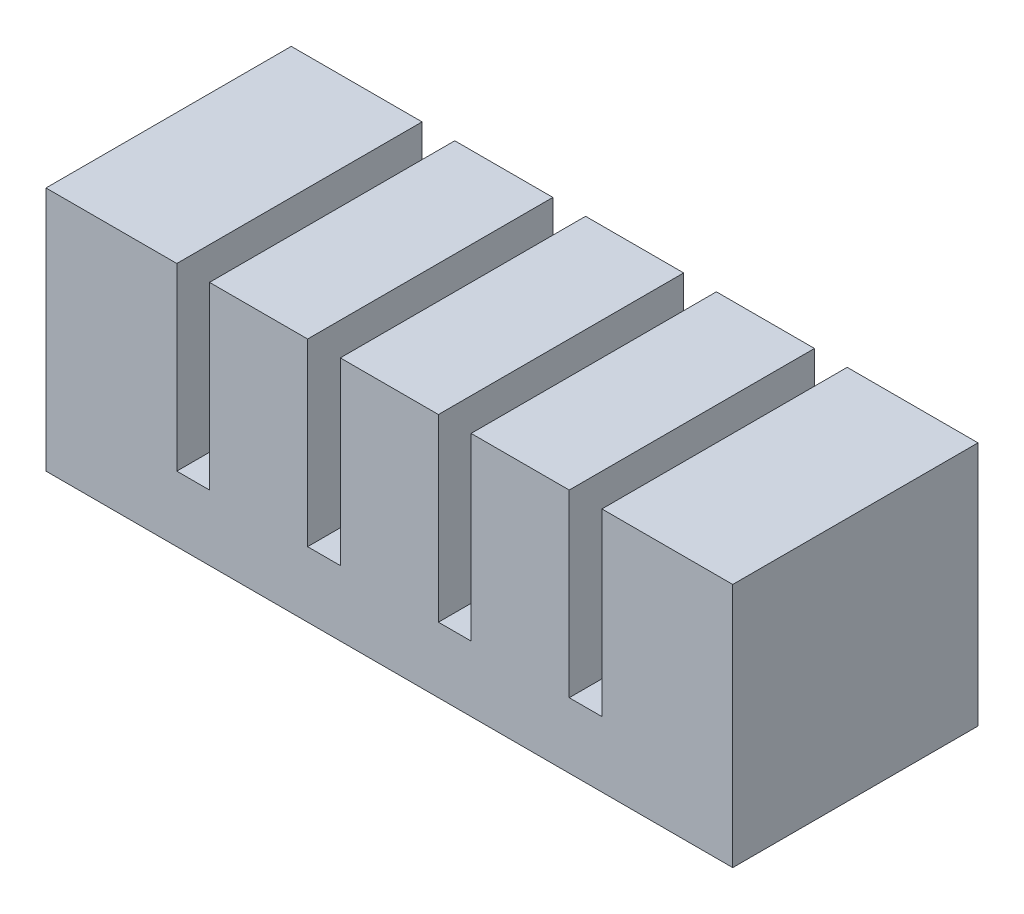
SolidWorks part; units mm, degrees
ref_plane "Front Plane" through (0, 0, 0) normal (0, 0, 1) x (1, 0, 0)
ref_plane "Top Plane" through (0, 0, 0) normal (0, 1, 0) x (1, 0, 0)
ref_plane "Right Plane" through (0, 0, 0) normal (1, 0, 0) x (0, 0, -1)
sketch "Sketch1" plane through (0, 0, 0) normal (0, 1, 0) x (1, 0, 0)
  line L1 (0, 0) -> (6, 0)
  line L2 (0, 0) -> (0, 15)
  line L3 (0, 15) -> (6, 15)
  line L4 (6, 0) -> (6, 15)
extrude "Boss-Extrude1" add sketch "Sketch1" along normal blind 15
sketch "Sketch2" plane through (0, 0, 0) normal (0, -1, 0) x (1, 0, 0)
  line L0 (6, 0) -> (6, -15) construction
  line L1 (5, -2) -> (1, -2)
  line L2 (5, -2) -> (5, -13)
  line L3 (5, -13) -> (1, -13)
  line L4 (1, -2) -> (1, -13)
  line L5 (0, -15) -> (0, 0) construction
  line L6 (0, 0) -> (6, 0) construction
  line L7 (6, -15) -> (0, -15) construction
  dimension "D1" = 1
  dimension "D2" = 1
  dimension "D3" = 2
  dimension "D4" = 2
extrude "Cut-Extrude1" cut sketch "Sketch2" against normal blind 13
sketch "Sketch3" plane through (0, 0, 0) normal (-1, 0, 0) x (0, 0, 1)
  line L0 (0, 15) -> (0, 0) construction
  line L1 (-15, 0) -> (0, 0)
  line L2 (-15, 0) -> (-15, 4)
  line L3 (-15, 4) -> (0, 4)
  line L4 (0, 0) -> (0, 4)
extrude "Boss-Extrude2" add sketch "Sketch3" along normal blind 2
pattern_linear "LPattern1" count 4 spacing 8 along (-1, 0, 0) of "Boss-Extrude2", "Boss-Extrude1", "Cut-Extrude1"
sketch "Sketch4" plane through (-26, 0, 0) normal (-1, 0, 0) x (0, 0, 1)
  line L1 (0, 0) -> (-15, 0)
  line L2 (0, 0) -> (0, 15)
  line L3 (0, 15) -> (-15, 15)
  line L4 (-15, 0) -> (-15, 15)
extrude "Boss-Extrude3" add sketch "Sketch4" along normal blind 8
sketch "Sketch5" plane through (0, 0, 0) normal (0, -1, 0) x (1, 0, 0)
  line L0 (-23, -2) -> (-23, -13) construction
  line L1 (-27, -2) -> (-31, -2)
  line L2 (-27, -2) -> (-27, -13)
  line L3 (-27, -13) -> (-31, -13)
  line L4 (-31, -2) -> (-31, -13)
  line L5 (-34, 0) -> (-18, 0) construction
  dimension "D1" = 4
  dimension "D2" = 2
extrude "Cut-Extrude2" cut sketch "Sketch5" against normal blind 5.5
combine bodies "Combine1" operation type add bodies to combine 104 105 132 103
sketch "Sketch6" plane through (6, 0, 0) normal (1, 0, 0) x (0, 0, -1)
  line L0 (0, 15) -> (15, 15) construction
  line L1 (15, 0) -> (0, 0)
  line L2 (15, 0) -> (15, 15)
  line L3 (15, 15) -> (0, 15)
  line L4 (0, 0) -> (0, 15)
  line L5 (0, 15) -> (0, 0) construction
extrude "Boss-Extrude4" add sketch "Sketch6" along normal blind 2
ref_point "Point1"
sketch "Sketch7" plane through (0, 0, 0) normal (0, -1, 0) x (1, 0, 0)
  line L1 (5, -8.5) -> (-31, -8.5)
  line L2 (5, -8.5) -> (5, -6.5)
  line L3 (5, -6.5) -> (-31, -6.5)
  line L4 (-31, -8.5) -> (-31, -6.5)
  line L5 (5, -8.5) -> (-31, -6.5) construction
  line L6 (5, -6.5) -> (-31, -8.5) construction
  point P0 (-13, -7.5)
extrude "Cut-Extrude3" cut sketch "Sketch7" against normal blind 2
ref_plane "Plane2" through (8, 15, -15) normal (0, 0, 1) x (1, 0, 0)
